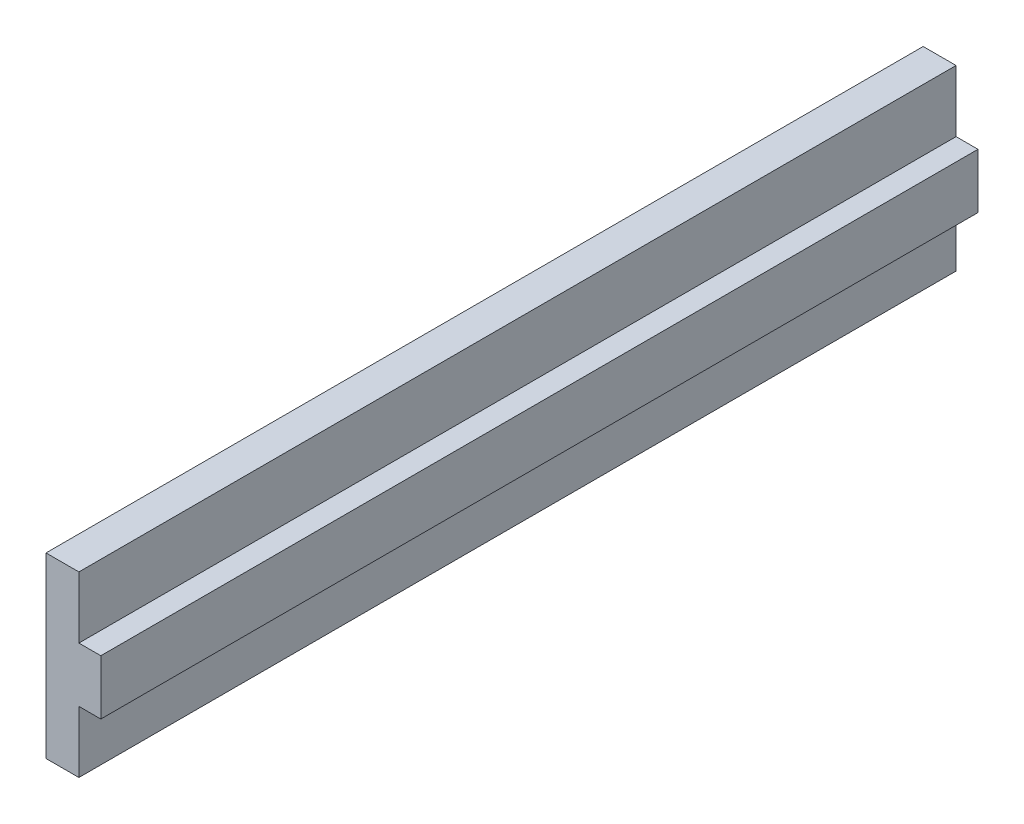
SolidWorks part; units mm, degrees
ref_plane "Front Plane" through (0, 0, 0) normal (0, 0, 1) x (1, 0, 0)
ref_plane "Top Plane" through (0, 0, 0) normal (0, 1, 0) x (1, 0, 0)
ref_plane "Right Plane" through (0, 0, 0) normal (1, 0, 0) x (0, 0, -1)
sketch "Sketch1" plane through (0, 0, 0) normal (0, 0, 1) x (1, 0, 0)
  line L0 (0, 0) -> (0, 20.6248)
  line L1 (0, 20.6248) -> (3.81, 20.6248)
  line L2 (3.81, 20.6248) -> (3.81, 13.4874)
  line L3 (3.81, 13.4874) -> (6.35, 13.4874)
  line L4 (6.35, 13.4874) -> (6.35, 7.1374)
  line L5 (6.35, 7.1374) -> (3.81, 7.1374)
  line L6 (3.81, 7.1374) -> (3.81, 0)
  line L7 (3.81, 0) -> (0, 0)
  dimension "D1" = 20.6248
  dimension "D2" = 3.81
  dimension "D3" = 3.81
  dimension "D4" = 6.35
  dimension "D5" = 2.54
extrude "Boss-Extrude1" add sketch "Sketch1" along normal blind 101.6
